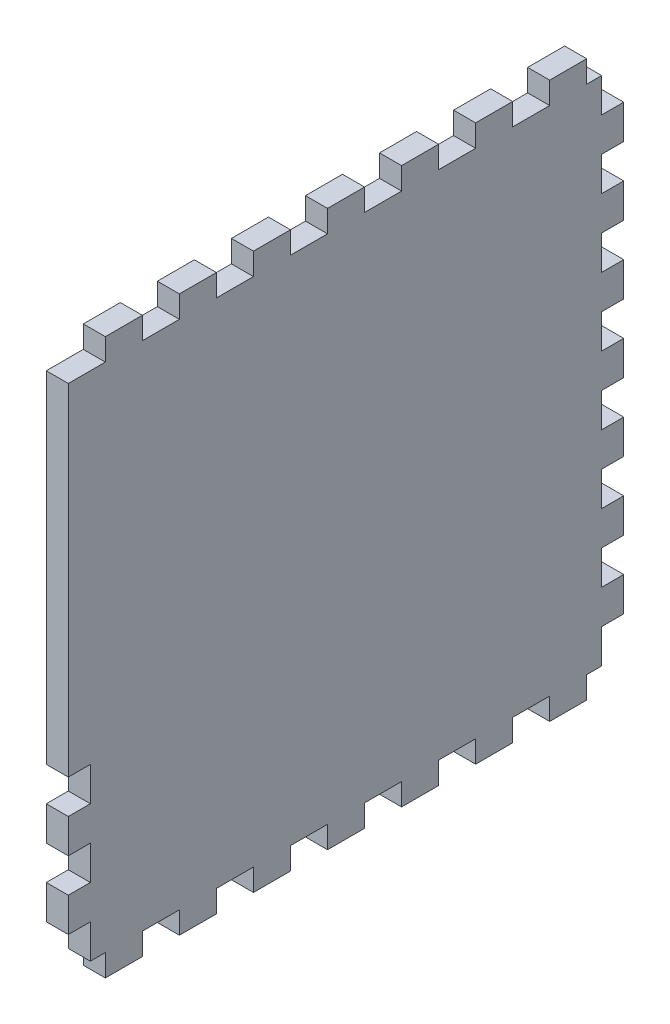
SolidWorks part; units mm, degrees
material "Acrylic (Medium-high impact)"
ref_plane "Front Plane" through (0, 0, 0) normal (0, 0, 1) x (1, 0, 0)
ref_plane "Top Plane" through (0, 0, 0) normal (0, 1, 0) x (1, 0, 0)
ref_plane "Right Plane" through (0, 0, 0) normal (1, 0, 0) x (0, 0, -1)
sketch "Sketch2" plane through (0, 0, 0) normal (1, 0, 0) x (0, 0, -1)
  line L1 (-40, -40) -> (40, -40)
  line L2 (-40, -40) -> (-40, 40)
  line L3 (-40, 40) -> (40, 40)
  line L4 (40, -40) -> (40, 40)
  line L5 (-40, -40) -> (40, 40) construction
  line L6 (-40, 40) -> (40, -40) construction
  point P0 (0, 0)
  dimension "D1" = 80
  dimension "D2" = 80
extrude "Boss-Extrude1" add sketch "Sketch2" along normal blind 3.175
sketch "Sketch3" plane through (3.175, 0, 0) normal (1, 0, 0) x (0, 0, -1)
  line L0 (0, 0) -> (50000, 0) construction
  line L1 (40, -40) -> (40, 40) construction
  line L2 (0, 0) -> (0, 50000) construction
  line L3 (40, 40) -> (-40, 40) construction
  line L6 (-36.825, 36.825) -> (-34.6667, 36.825)
  line L7 (-34.6667, 36.825) -> (-34.6667, 40)
  line L8 (-34.6667, 40) -> (-29.3333, 40)
  line L9 (-24, 40) -> (-18.6667, 40)
  line L10 (-24, 36.825) -> (-24, 40)
  line L11 (-29.3333, 36.825) -> (-24, 36.825)
  line L12 (-29.3333, 40) -> (-29.3333, 36.825)
  line L13 (-13.3333, 40) -> (-8, 40)
  line L14 (-13.3333, 36.825) -> (-13.3333, 40)
  line L15 (-18.6667, 36.825) -> (-13.3333, 36.825)
  line L16 (-18.6667, 40) -> (-18.6667, 36.825)
  line L17 (-2.6667, 40) -> (2.6667, 40)
  line L18 (-2.6667, 36.825) -> (-2.6667, 40)
  line L19 (-8, 36.825) -> (-2.6667, 36.825)
  line L20 (-8, 40) -> (-8, 36.825)
  line L21 (8, 40) -> (13.3333, 40)
  line L22 (8, 36.825) -> (8, 40)
  line L23 (2.6667, 36.825) -> (8, 36.825)
  line L24 (2.6667, 40) -> (2.6667, 36.825)
  line L25 (18.6667, 40) -> (24, 40)
  line L26 (18.6667, 36.825) -> (18.6667, 40)
  line L27 (13.3333, 36.825) -> (18.6667, 36.825)
  line L28 (13.3333, 40) -> (13.3333, 36.825)
  line L29 (29.3333, 40) -> (34.6667, 40)
  line L30 (29.3333, 36.825) -> (29.3333, 40)
  line L31 (24, 36.825) -> (29.3333, 36.825)
  line L32 (24, 40) -> (24, 36.825)
  line L33 (34.6667, -40) -> (34.6667, -36.825)
  line L34 (-40, -40) -> (40, -40) construction
  line L35 (34.6667, 36.825) -> (36.825, 36.825)
  line L36 (34.6667, 40) -> (34.6667, 36.825)
  line L37 (34.6667, -36.825) -> (36.825, -36.825)
  line L38 (-40, 40) -> (-40, -40) construction
  line L39 (24, -40) -> (24, -36.825)
  line L40 (24, -36.825) -> (29.3333, -36.825)
  line L41 (29.3333, -36.825) -> (29.3333, -40)
  line L42 (29.3333, -40) -> (34.6667, -40)
  line L43 (13.3333, -40) -> (13.3333, -36.825)
  line L44 (13.3333, -36.825) -> (18.6667, -36.825)
  line L45 (18.6667, -36.825) -> (18.6667, -40)
  line L46 (18.6667, -40) -> (24, -40)
  line L47 (2.6667, -40) -> (2.6667, -36.825)
  line L48 (2.6667, -36.825) -> (8, -36.825)
  line L49 (8, -36.825) -> (8, -40)
  line L50 (8, -40) -> (13.3333, -40)
  line L51 (-8, -40) -> (-8, -36.825)
  line L52 (-8, -36.825) -> (-2.6667, -36.825)
  line L53 (-2.6667, -36.825) -> (-2.6667, -40)
  line L54 (-2.6667, -40) -> (2.6667, -40)
  line L55 (-18.6667, -40) -> (-18.6667, -36.825)
  line L56 (-18.6667, -36.825) -> (-13.3333, -36.825)
  line L57 (-13.3333, -36.825) -> (-13.3333, -40)
  line L58 (-13.3333, -40) -> (-8, -40)
  line L59 (-29.3333, -40) -> (-29.3333, -36.825)
  line L60 (-29.3333, -36.825) -> (-24, -36.825)
  line L61 (-24, -36.825) -> (-24, -40)
  line L62 (-24, -40) -> (-18.6667, -40)
  line L63 (-34.6667, -40) -> (-29.3333, -40)
  line L64 (-34.6667, -36.825) -> (-34.6667, -40)
  line L65 (-36.825, -36.825) -> (-34.6667, -36.825)
  line L68 (36.825, 36.825) -> (36.825, 31.915)
  line L69 (36.825, 31.915) -> (40, 31.915)
  line L70 (40, 31.915) -> (40, 27.005)
  line L71 (36.825, 27.005) -> (36.825, 22.095)
  line L72 (36.825, 27.005) -> (40, 27.005)
  line L73 (36.825, 22.095) -> (40, 22.095)
  line L74 (40, 22.095) -> (40, 17.185)
  line L75 (36.825, 17.185) -> (36.825, 12.275)
  line L76 (36.825, 17.185) -> (40, 17.185)
  line L77 (36.825, 12.275) -> (40, 12.275)
  line L78 (40, 12.275) -> (40, 7.365)
  line L79 (36.825, 7.365) -> (36.825, 2.455)
  line L80 (36.825, 7.365) -> (40, 7.365)
  line L81 (36.825, 2.455) -> (40, 2.455)
  line L82 (40, 2.455) -> (40, -2.455)
  line L83 (36.825, -2.455) -> (36.825, -7.365)
  line L84 (36.825, -2.455) -> (40, -2.455)
  line L85 (36.825, -7.365) -> (40, -7.365)
  line L86 (40, -7.365) -> (40, -12.275)
  line L87 (36.825, -12.275) -> (36.825, -17.185)
  line L88 (36.825, -12.275) -> (40, -12.275)
  line L89 (36.825, -17.185) -> (40, -17.185)
  line L90 (40, -17.185) -> (40, -22.095)
  line L91 (36.825, -22.095) -> (36.825, -27.005)
  line L92 (36.825, -22.095) -> (40, -22.095)
  line L93 (36.825, -27.005) -> (40, -27.005)
  line L94 (40, -27.005) -> (40, -31.915)
  line L95 (36.825, -31.915) -> (36.825, -36.825)
  line L96 (36.825, -31.915) -> (40, -31.915)
  line L101 (-36.825, -31.915) -> (-40, -31.915)
  line L117 (40, -36.825) -> (40, -41.735) [skipped]
  line L118 (-36.825, -31.915) -> (-36.825, -36.825)
  line L119 (-40, -27.005) -> (-40, -31.915)
  line L120 (-36.825, -27.005) -> (-40, -27.005)
  line L121 (-36.825, -22.095) -> (-40, -22.095)
  line L122 (-36.825, -22.095) -> (-36.825, -27.005)
  line L123 (-40, -17.185) -> (-40, -22.095)
  line L124 (-36.825, -17.185) -> (-40, -17.185)
  line L125 (-36.825, -12.275) -> (-40, -12.275)
  line L126 (-36.825, -12.275) -> (-36.825, -17.185)
  line L127 (-40, -7.365) -> (-40, -12.275)
  line L128 (-36.825, -7.365) -> (-40, -7.365)
  line L129 (-36.825, -2.455) -> (-40, -2.455)
  line L130 (-36.825, -2.455) -> (-36.825, -7.365)
  line L131 (-40, 2.455) -> (-40, -2.455)
  line L132 (-36.825, 2.455) -> (-40, 2.455)
  line L133 (-36.825, 7.365) -> (-40, 7.365)
  line L134 (-36.825, 7.365) -> (-36.825, 2.455)
  line L135 (-40, 12.275) -> (-40, 7.365)
  line L136 (-36.825, 12.275) -> (-40, 12.275)
  line L137 (-36.825, 17.185) -> (-40, 17.185)
  line L138 (-36.825, 17.185) -> (-36.825, 12.275)
  line L139 (-40, 22.095) -> (-40, 17.185)
  line L140 (-36.825, 22.095) -> (-40, 22.095)
  line L141 (-36.825, 27.005) -> (-40, 27.005)
  line L142 (-36.825, 27.005) -> (-36.825, 22.095)
  line L143 (-40, 31.915) -> (-40, 27.005)
  line L144 (-36.825, 31.915) -> (-40, 31.915)
  line L145 (-36.825, 36.825) -> (-36.825, 31.915)
  line L149 (36.825, -36.825) -> (40, -36.825) [skipped]
  point P5 (40, 0)
  point P10 (0, 40)
  dimension "D1" = 3.175
  dimension "D2" = 3.175
  dimension "D3" = 3.175
  dimension "D6" = 8
extrude "Cut-Extrude1" cut sketch "Sketch3" against normal through all flip side to cut
sketch "Sketch5" plane through (0, 0, 0) normal (-1, 0, 0) x (0, 0, 1)
  line L1 (36.825, 36.825) -> (40, 36.825)
  line L2 (36.825, 36.825) -> (36.825, -7.365)
  line L3 (36.825, -7.365) -> (40, -7.365)
  line L4 (40, 36.825) -> (40, -7.365)
extrude "Boss-Extrude3" add sketch "Sketch5" against normal up to surface (3.175 mm away) up to face at (3.175, 0, 0)
